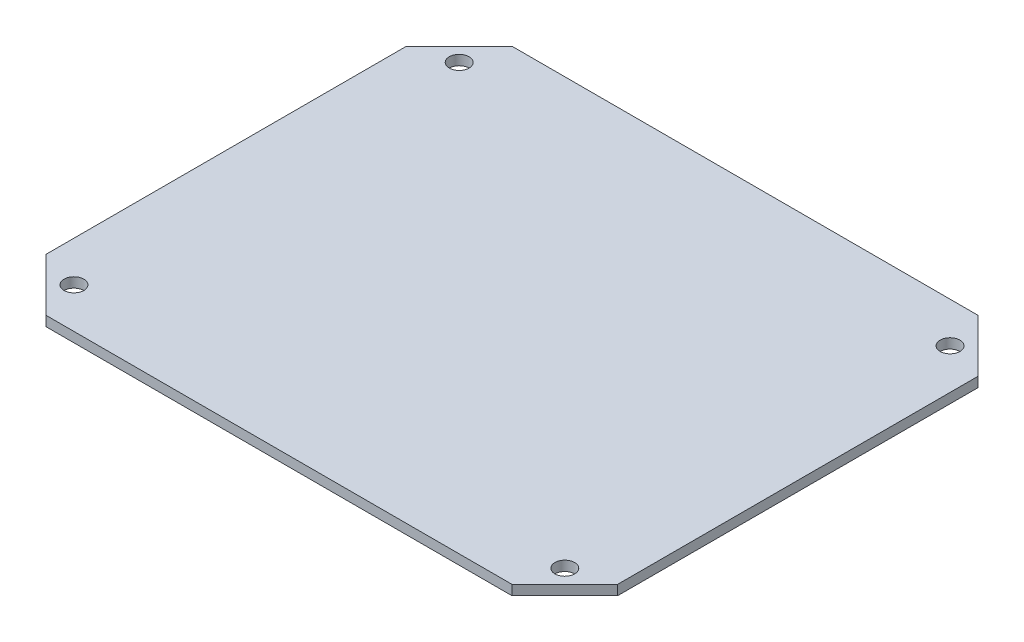
SolidWorks part; units mm, degrees
ref_plane "Front Plane" through (0, 0, 0) normal (0, 0, 1) x (1, 0, 0)
ref_plane "Top Plane" through (0, 0, 0) normal (0, 1, 0) x (1, 0, 0)
ref_plane "Right Plane" through (0, 0, 0) normal (1, 0, 0) x (0, 0, -1)
sketch "Sketch1" plane through (0, 0, 0) normal (0, 1, 0) x (1, 0, 0)
  line L1 (-46, -37.5) -> (46, -37.5)
  line L2 (-46, -37.5) -> (-46, 37.5)
  line L3 (-46, 37.5) -> (46, 37.5)
  line L4 (46, -37.5) -> (46, 37.5)
  line L5 (-46, -37.5) -> (46, 37.5) construction
  line L6 (-46, 37.5) -> (46, -37.5) construction
  point P0 (0, 0)
  dimension "D1" = 92
  dimension "D2" = 75
extrude "Boss-Extrude1" add sketch "Sketch1" along normal blind 1.59 contours L2 L3 L4 L1
chamfer "Chamfer1" distance 8.5 angle 45 4 edges at (-46, 0.795, 37.5) (-46, 0.795, -37.5) (46, 0.795, -37.5) (46, 0.795, 37.5)
hole_wizard "Ø1.0mm Dowel Hole1" positions "Sketch2" profile "Sketch3" hole size "Ø1.0" standard "ANSI Metric" end condition up to next
sketch "Sketch2" plane through (0, 1.59, 0) normal (0, 1, 0) x (1, 0, 0)
  line L0 (-46, -29) -> (-46, 29) construction
  line L1 (-37.5, 37.5) -> (37.5, 37.5) construction
  line L2 (-37.5, -37.5) -> (37.5, -37.5) construction
  line L3 (46, -29) -> (46, 29) construction
  point P0 (-39.5, 31)
  point P2 (39.5, 31)
  point P4 (39.5, -31)
  point P6 (-39.5, -31)
  point P17 (0, 0)
  point P18 (0, 0)
  point P19 (0, 0)
  dimension "D1" = 6.5
  dimension "D2" = 6.5
  dimension "D3" = 6.5
  dimension "D4" = 6.5
sketch "Sketch3" plane through (-39.5, 1.59, -31) normal (1, 0, 0) x (0, 0, 1)
  line L0 (0, 0) -> (0, 1.59)
  line L1 (0, 1.59) -> (1.59, 1.59)
  line L2 (1.59, 1.59) -> (1.59, 0)
  line L5 (1.59, 0) -> (0, 0)
  line L11 (0, -6.35) -> (0, 107.95) construction
  dimension "Thru Hole Dia." = 3.18
  dimension "Thru Hole Depth" = 1.59
